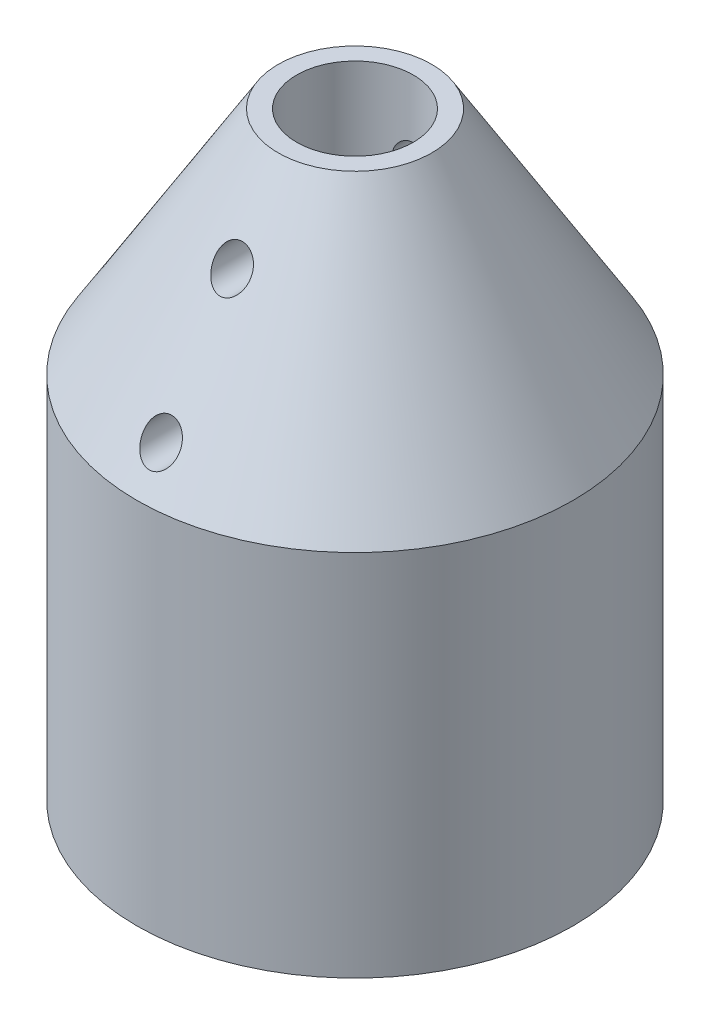
SolidWorks part; units mm, degrees
ref_plane "前视基准面" through (0, 0, 0) normal (0, 0, 1) x (1, 0, 0)
ref_plane "上视基准面" through (0, 0, 0) normal (0, 1, 0) x (1, 0, 0)
ref_plane "右视基准面" through (0, 0, 0) normal (1, 0, 0) x (0, 0, -1)
sketch "草图1" plane through (0, 0, 0) normal (0, 0, 1) x (1, 0, 0)
  line L0 (0, 0) -> (0, 30.48)
  line L1 (0, 0) -> (0, 67.4429) construction
  line L2 (18.034, 30.48) -> (18.034, 0)
  line L3 (18.034, 0) -> (0, 0)
  line L4 (6.35, 49.53) -> (18.034, 30.48)
  line L14 (0, 30.48) -> (0, 49.53)
  line L15 (0, 49.53) -> (6.35, 49.53)
  dimension "D1" = 30.48
  dimension "D2" = 18.034
  dimension "D3" = 19.05
  dimension "D4" = 6.35
revolve "旋转1" add sketch "草图1" angle 360 about L1
sketch "Sketch3" plane through (0, 49.53, 0) normal (0, 1, 0) x (1, 0, 0)
  circle A0 centre (0, 0) radius 4.826
  dimension "D1" = 9.652
extrude "Cut-Extrude1" cut sketch "Sketch3" against normal blind 25.4
sketch "Sketch4" plane through (0, 0, 0) normal (0, 0, 1) x (1, 0, 0)
  line L0 (6.35, 49.53) -> (-6.35, 49.53) construction
  circle A0 centre (0, 43.18) radius 1.5
  circle A1 centre (0, 33.655) radius 1.5
  dimension "D1" = 3
  dimension "D2" = 3
  dimension "D3" = 9.525
  dimension "D4" = 6.35
extrude "Cut-Extrude2" cut sketch "Sketch4" against normal through all and the other way through all
sketch "Sketch5" plane through (0, 0, 0) normal (0, -1, 0) x (1, 0, 0)
  circle A0 centre (0, 9.525) radius 1.5
  dimension "D1" = 3
  dimension "D2" = 9.525
extrude "Cut-Extrude3" cut sketch "Sketch5" against normal blind 6.35
pattern_circular "CirPattern1" count 8 over 360 about axis through (0, 0, 0) along (0, 1, 0) of "Cut-Extrude3"
sketch "Sketch6" plane through (0, 0, 0) normal (0, -1, 0) x (1, 0, 0)
  circle A0 centre (0, 0) radius 4.7625
  dimension "D1" = 9.525
extrude "Boss-Extrude1" add sketch "Sketch6" along normal blind 9.525
chamfer "Chamfer1" distance 0.635 angle 45 1 edges at (0, -9.525, -4.7625)
sketch "Sketch7" plane through (0, 0, 0) normal (0, 0, 1) x (1, 0, 0)
  line L0 (0, 0) -> (0, -12.5047) construction
  line L1 (-5.588, 0) -> (-4.7625, -2.2225)
  line L2 (-18.034, 0) -> (18.034, 0) construction
  line L3 (-4.7625, 0) -> (-4.7625, -8.89) construction
  line L4 (-4.7625, -2.2225) -> (-4.7625, 0)
  line L5 (-4.7625, 0) -> (4.7625, 0) construction
  line L6 (-4.7625, 0) -> (-5.588, 0)
  dimension "D1" = 5.588
  dimension "D2" = 2.2225
revolve "Revolve1" add sketch "Sketch7" angle 360 about L0
